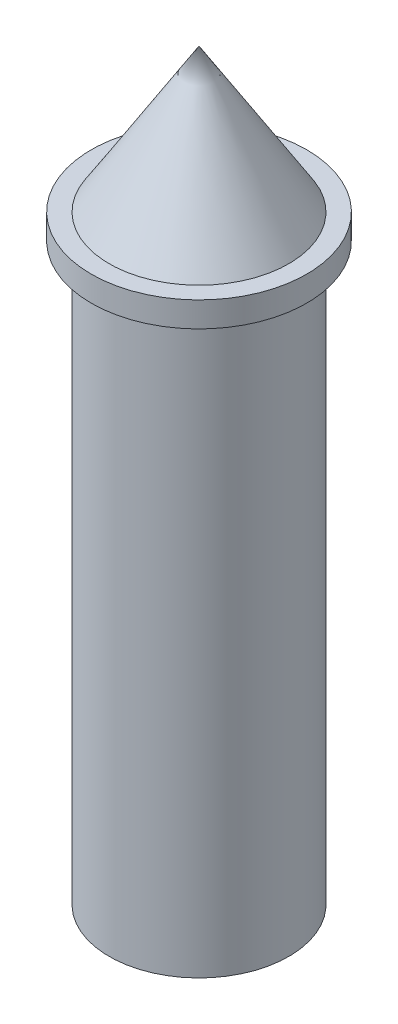
SolidWorks part; units mm, degrees
material "PPS"
ref_plane "Front Plane" through (0, 0, 0) normal (0, 0, 1) x (1, 0, 0)
ref_plane "Top Plane" through (0, 0, 0) normal (0, 1, 0) x (1, 0, 0)
ref_plane "Right Plane" through (0, 0, 0) normal (1, 0, 0) x (0, 0, -1)
sketch "Sketch1" plane through (0, 0, 0) normal (0, 0, 1) x (1, 0, 0)
  line L0 (31.75, 212.09) -> (0, 262.89)
  line L1 (0, 0) -> (31.75, 0)
  line L2 (0, 0) -> (0, 212.09)
  line L3 (0, 212.09) -> (0, 262.89)
  line L4 (31.75, 0) -> (31.75, 203.2)
  line L5 (31.75, 203.2) -> (38.1, 203.2)
  line L6 (31.75, 212.09) -> (38.1, 212.09)
  line L8 (38.1, 203.2) -> (38.1, 212.09)
  point P6 (25.4, 253.7055)
  dimension "D1" = 203.2
  dimension "D2" = 31.75
  dimension "D3" = 8.89
  dimension "D4" = 6.35
  dimension "D5" = 50.8
revolve "Revolve1" add sketch "Sketch1" angle 360 about L2
